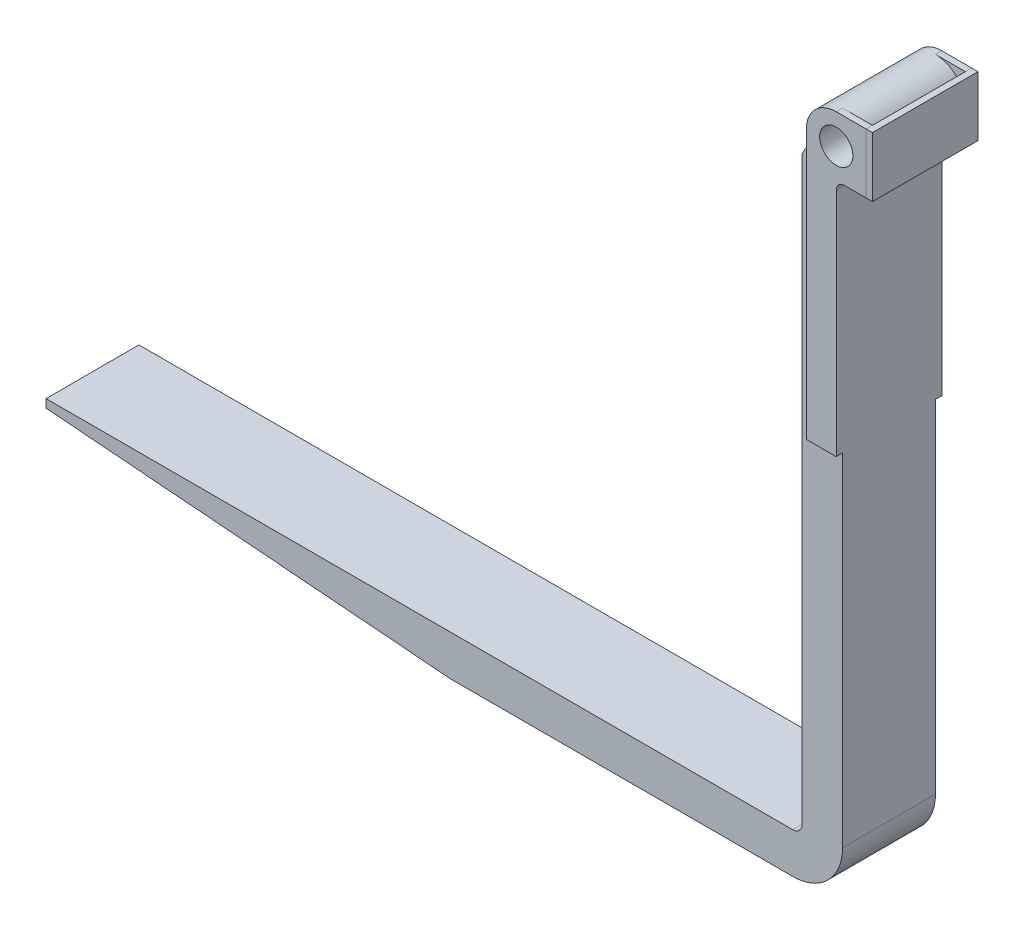
SolidWorks part; units mm, degrees
ref_plane "Front Plane" through (0, 0, 0) normal (0, 0, 1) x (1, 0, 0)
ref_plane "Top Plane" through (0, 0, 0) normal (0, 1, 0) x (1, 0, 0)
ref_plane "Right Plane" through (0, 0, 0) normal (1, 0, 0) x (0, 0, -1)
sketch "Sketch1" plane through (0, 0, 0) normal (0, 0, 1) x (1, 0, 0)
  line L0 (0, 950) -> (0, 75)
  line L1 (-75, 0) -> (-1200, 0)
  arc A0 (0, 75) -> (-75, 0) centre (-75, 75) cw
  point P6 (0, 0)
  dimension "D3" = 75
  dimension "D1" = 950
  dimension "D2" = 1200
extrude "Extrude-Thin1" add sketch "Sketch1" along normal mid plane 140 thin
sketch "Sketch2" plane through (0, 0, 70) normal (0, 0, 1) x (1, 0, 0)
  line L0 (-1200, 48.5) -> (-590, 0)
  line L1 (-1200, 0) -> (-1200, 61) construction
  line L2 (-75, 0) -> (-1200, 0) construction
  line L3 (-75, 61) -> (-1200, 61) construction
  dimension "D1" = 12.5
  dimension "D2" = 610
extrude "Cut-Extrude1" cut sketch "Sketch2" against normal through all and the other way through all flip side to cut
sketch "Sketch3" plane through (0, 0, 0) normal (0, 0, 1) x (1, 0, 0)
  line L0 (0, 950) -> (0, 995) construction
  circle A0 centre (0, 995) radius 45
  circle A1 centre (0, 995) radius 25
  dimension "D1" = 50
  dimension "D2" = 90
extrude "Boss-Extrude1" add sketch "Sketch3" along normal mid plane 140 separate body
sketch "Sketch4" plane through (0, 0, 0) normal (0, 0, 1) x (1, 0, 0)
  line L0 (-61, 950) -> (0, 950) construction
  line L1 (-61, 950) -> (0, 950)
  line L2 (-61, 950) -> (-43.0692, 981.9598)
  circle A0 centre (0, 995) radius 45 construction
  arc A1 (-43.0692, 981.9598) -> (0, 950) centre (0, 995) ccw
  point P5 (0, 0)
extrude "Boss-Extrude2" add sketch "Sketch4" along normal mid plane 140 separate body
sketch "Sketch5" plane through (0, 0, 70) normal (0, 0, 1) x (1, 0, 0)
  line L0 (-45, 995) -> (-45, 590)
  line L1 (-45, 590) -> (0, 590)
  line L2 (0, 950) -> (0, 75) construction
  line L3 (0, 590) -> (0, 937.5)
  line L4 (12.5, 950) -> (45, 950)
  line L5 (45, 950) -> (45, 1040)
  line L6 (45, 1040) -> (0, 1040)
  circle A0 centre (0, 995) radius 45 construction
  arc A1 (0, 1040) -> (-45, 995) centre (0, 995) ccw
  arc A2 (0, 937.5) -> (12.5, 950) centre (12.5, 937.5) cw
  point P14 (0, 950)
  circle M3 centre (0, 995) radius 45
  circle M4 centre (0, 995) radius 25
  dimension "D1" = 12.5
  dimension "D2" = 45
  dimension "D3" = 450
extrude "Boss-Extrude3" add sketch "Sketch5" along normal blind 9.5 contours L5 L6 M3 | M3 M4 | L3 A2 L4 L5 L0 L1 M3
mirror "Mirror1" about plane through (0, 0, 0) normal (0, 0, 1) of "Boss-Extrude3"
sketch "Sketch6" plane through (45, 0, 0) normal (1, 0, 0) x (0, 0, -1)
  line L1 (-79.5, 1040) -> (79.5, 1040)
  line L2 (-79.5, 1040) -> (-79.5, 950)
  line L3 (-79.5, 950) -> (79.5, 950)
  line L4 (79.5, 1040) -> (79.5, 950)
extrude "Boss-Extrude4" add sketch "Sketch6" along normal blind 9.5 separate body
